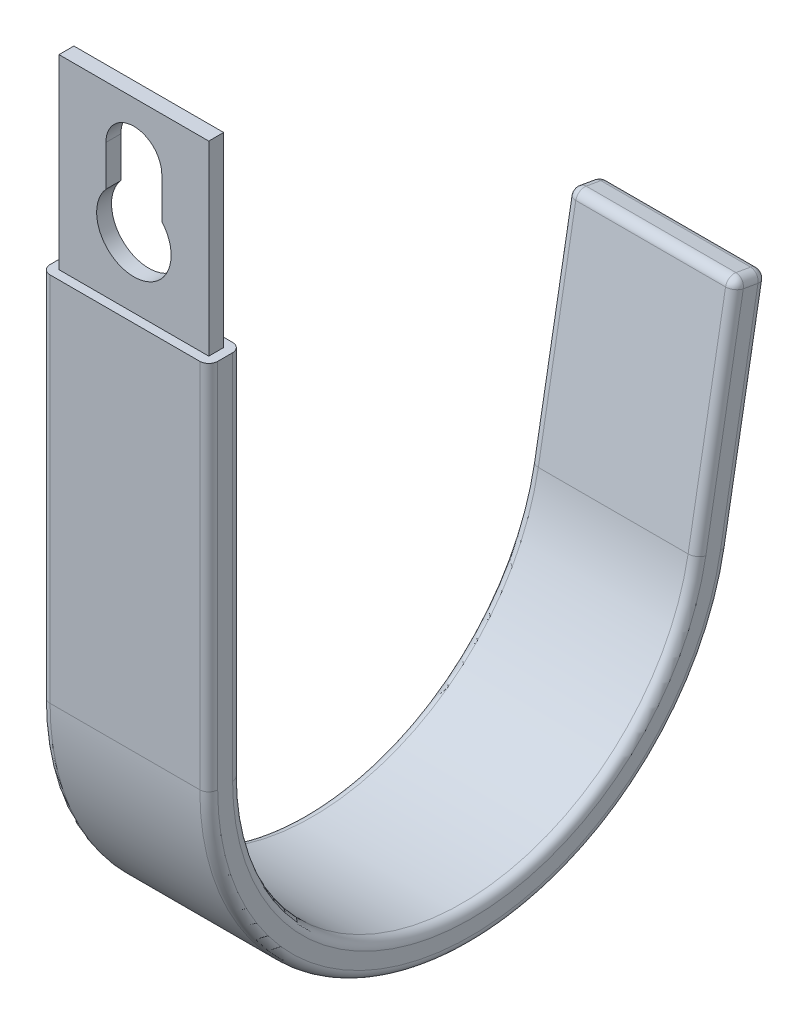
SolidWorks part; units mm, degrees
ref_plane "Front" through (0, 0, 0) normal (0, 0, 1) x (1, 0, 0)
ref_plane "Top" through (0, 0, 0) normal (0, 1, 0) x (1, 0, 0)
ref_plane "Right" through (0, 0, 0) normal (1, 0, 0) x (0, 0, -1)
sketch "Sketch1" plane through (0, 0, 0) normal (1, 0, 0) x (0, 0, -1)
  line L0 (0, 94.996) -> (-2.54, 94.996) construction
  line L1 (0, 94.996) -> (0, 0)
  line L2 (80.6626, -7.0571) -> (87.3125, 30.6565)
  line L5 (40.64, -40.64) -> (40.64, -44.704) construction
  arc A0 (0, 0) -> (80.6626, -7.0571) centre (40.64, 0) ccw
  dimension "D4" = 10
  dimension "D5" = 87.3125
  dimension "D1" = 2.54
  dimension "D3" = 40.64
  dimension "D2" = 139.7
  dimension "D7" = 4.064
ref_plane "Plane1" through (0, 94.996, 0) normal (0, 1, 0) x (1, 0, 0)
sketch "Sketch2" plane through (0, 94.996, -15.113) normal (0, -1, 0) x (1, 0, 0)
  line L1 (-12.7635, 17.653) -> (12.7635, 17.653)
  line L2 (-12.7635, 17.653) -> (-12.7635, 15.113)
  line L3 (-12.7635, 15.113) -> (12.7635, 15.113)
  line L4 (12.7635, 17.653) -> (12.7635, 15.113)
  point P4 (0, 17.653)
  dimension "D1" = 25.527
sweep "Sweep1" add profiles "Sketch2" path "Sketch1"
sketch "Sketch5" plane through (0, 0, 0) normal (1, 0, 0) x (0, 0, -1)
  line L0 (0, 0) -> (0, 63.246)
  line L1 (0, 94.996) -> (0, 0) construction
  line L3 (80.6626, -7.0571) -> (87.3125, 30.6565) construction
  line L4 (80.6626, -7.0571) -> (87.3125, 30.6565)
  arc A0 (0, 0) -> (80.6626, -7.0571) centre (40.64, 0) ccw construction
  arc A1 (0, 0) -> (80.6626, -7.0571) centre (40.64, 0) ccw
  dimension "D1" = 31.75
sketch "Sketch6" plane through (0, 44.6634, -7.8754) normal (0, 0.9848, -0.1736) x (1, 0, 0)
  line L0 (14.2875, 84.7266) -> (-14.2875, 84.7266)
  line L1 (-14.2875, 84.7266) -> (-14.2875, 79.1386)
  line L2 (-14.2875, 79.1386) -> (14.2875, 79.1386)
  line L3 (14.2875, 79.1386) -> (14.2875, 84.7266)
  line L4 (-12.7635, 83.2026) -> (-12.7635, 80.6626)
  line L5 (-12.7635, 80.6626) -> (12.7635, 80.6626)
  line L6 (12.7635, 80.6626) -> (12.7635, 83.2026)
  line L7 (12.7635, 83.2026) -> (-12.7635, 83.2026)
  line L8 (-12.7635, 83.2026) -> (-12.7635, 80.6626)
  line L9 (-12.7635, 80.6626) -> (12.7635, 80.6626)
  line L10 (12.7635, 80.6626) -> (12.7635, 83.2026)
  line L11 (12.7635, 83.2026) -> (-12.7635, 83.2026)
  dimension "D1" = 0
  dimension "D2" = 1.524
sweep "Sweep3" add profiles "Sketch6" path "Sketch5"
fillet "Fillet1" radius 1.524 16 edges at (-14.2875, 31.623, -1.524) (14.2875, 31.623, 4.064) (-14.2875, -38.9672, -37.2308) (14.2875, -44.5339, -36.7438) (14.2875, -38.9672, -37.2308) (14.2875, 31.623, -1.524) (14.2875, 11.094, -87.9898) (14.2875, 12.0643, -82.4867) (-14.2875, -44.5339, -36.7438) (-14.2875, 31.623, 4.064) (-14.2875, 12.0643, -82.4867) (-14.2875, 11.094, -87.9898) (14.2875, 30.4359, -88.5632) (0, 29.9508, -91.3148) (-14.2875, 30.4359, -88.5632) (0, 30.9211, -85.8117)
sketch "Sketch8" plane through (0, 0, 0) normal (1, 0, 0) x (0, 0, -1)
  line L1 (-4.064, 94.996) -> (91.0733, 94.996) construction
  line L2 (-4.064, 94.996) -> (-4.064, -44.704) construction
  line L3 (-4.064, -44.704) -> (91.0733, -44.704) construction
  line L4 (91.0733, 94.996) -> (91.0733, -44.704) construction
  arc A1 (91.0501, 28.4499) -> (89.8139, 30.2154) centre (89.5493, 28.7146) ccw construction
sketch "Sketch9" plane through (0, 0, 0) normal (0, 0, -1) x (-1, 0, 0)
  line L0 (0, 86.0334) -> (0, 74.9209) construction
  line L1 (4.7625, 86.0334) -> (4.7625, 79.121)
  line L2 (-4.7625, 86.0334) -> (-4.7625, 79.121)
  line L3 (0, 90.7959) -> (0, 68.5709) construction
  line L4 (0, 94.996) -> (0, 63.246) construction
  line L5 (12.7635, 94.996) -> (-12.7635, 94.996) construction
  line L6 (12.7635, 63.246) -> (-12.7635, 63.246) construction
  line L7 (-4.7625, 79.121) -> (4.7625, 79.121) construction
  arc A0 (-4.7625, 79.121) -> (4.7625, 79.121) centre (0, 74.9209) ccw
  arc A1 (4.7625, 86.0334) -> (-4.7625, 86.0334) centre (0, 86.0334) ccw
  point P3 (0, 79.121)
  point P5 (0, 79.121)
  point P17 (0, 79.121)
  dimension "D1" = 12.7
  dimension "D2" = 9.525
  dimension "D3" = 22.225
extrude "Cut-Extrude1" cut sketch "Sketch9" against normal through all
sketch "Sketch10" plane through (0, 0, 0) normal (0, 0, 1) x (1, 0, 0)
  circle A0 centre (0, 74.9209) radius 6.35 construction
  arc A1 (-4.7625, 79.121) -> (4.7625, 79.121) centre (0, 74.9209) ccw construction
